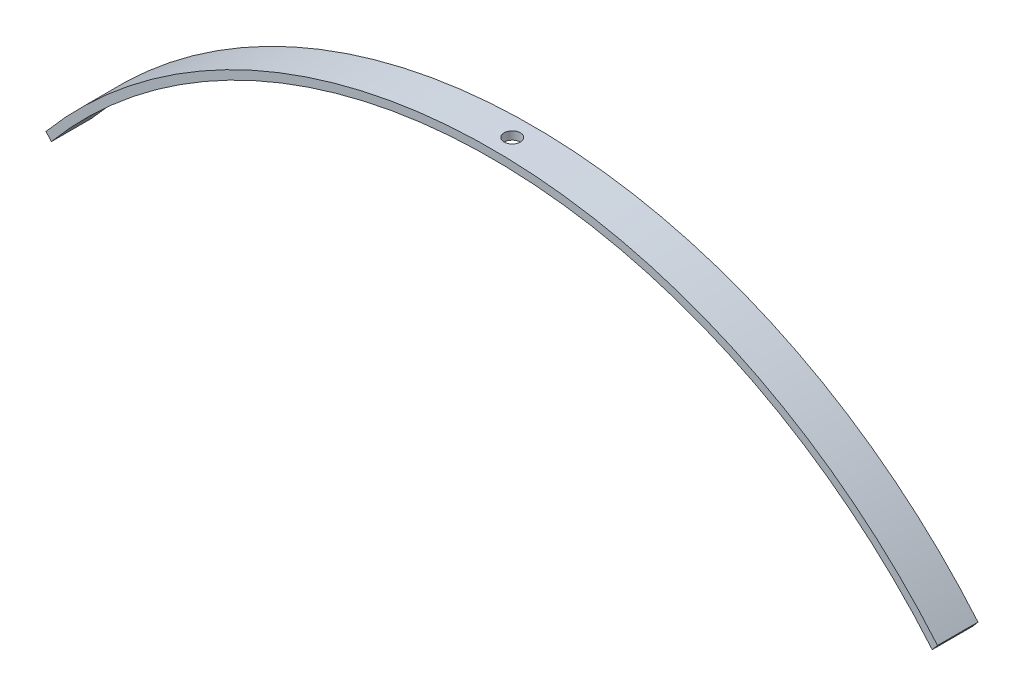
SolidWorks part; units mm, degrees
material "AISI 1020"
ref_plane "Face" through (0, 0, 0) normal (0, 0, 1) x (1, 0, 0)
ref_plane "Dessus" through (0, 0, 0) normal (0, 1, 0) x (1, 0, 0)
ref_plane "Droite" through (0, 0, 0) normal (1, 0, 0) x (0, 0, -1)
sketch "Esquisse2" plane through (0, 0, 0) normal (0, 0, 1) x (1, 0, 0)
  line L0 (0, 0) -> (0, 150) construction
  line L3 (-108.8907, 91.1417) -> (-110.1961, 92.6974)
  line L5 (108.7783, 91.2758) -> (110.0834, 92.8312)
  arc A0 (110.0834, 92.8312) -> (-110.1961, 92.6974) centre (0, 0) ccw
  arc A1 (108.7783, 91.2758) -> (-108.8907, 91.1417) centre (0, 0) ccw
  circle A3 centre (0, 0) radius 144 construction
  circle A4 centre (0, 0) radius 142 construction
  point P1 (143, 0)
  point P9 (138.6642, 42.3939)
  dimension "D1" = 288
  dimension "D5" = 40
  dimension "D6" = 40
  dimension "D2" = 2
extrude "Boss.-Extru.1" add sketch "Esquisse2" along normal blind 10
sketch "Esquisse3" plane through (0, 0, 0) normal (0, 1, 0) x (1, 0, 0)
  line L0 (110.0834, 0) -> (-110.1961, 0) construction
  circle A0 centre (0, -5) radius 2
  dimension "D1" = 5
  dimension "D2" = 4
extrude "Enlèv. mat.-Extru.1" cut sketch "Esquisse3" along normal up to next
